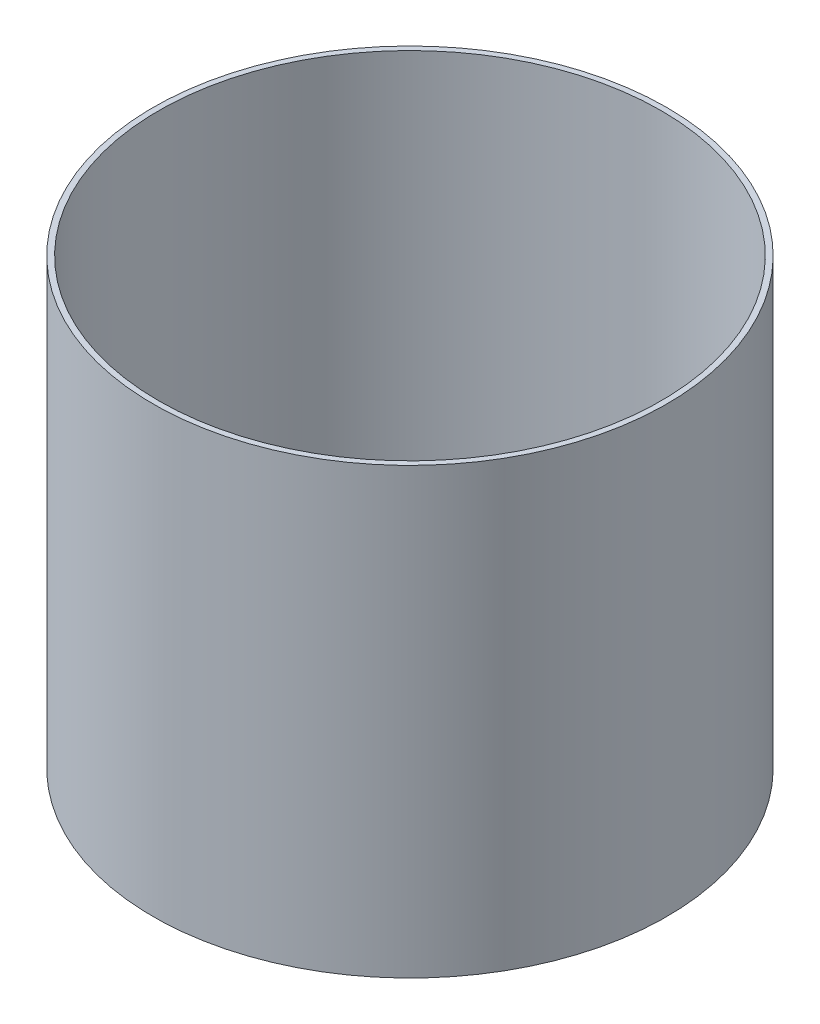
SolidWorks part; units mm, degrees
ref_plane "Front Plane" through (0, 0, 0) normal (0, 0, 1) x (1, 0, 0)
ref_plane "Top Plane" through (0, 0, 0) normal (0, 1, 0) x (1, 0, 0)
ref_plane "Right Plane" through (0, 0, 0) normal (1, 0, 0) x (0, 0, -1)
sketch "Sketch1" plane through (0, 0, 0) normal (0, 0, 1) x (1, 0, 0)
  line L0 (-85.7751, 73.1273) -> (-86.7751, 73.1273)
  line L1 (-86.7751, 73.1273) -> (-86.7751, -5.5436)
  line L2 (-86.7751, -5.5436) -> (-115, 1)
  line L3 (-115, 1) -> (-115, 0)
  line L4 (-115, 0) -> (-85.7751, -6.7754)
  line L5 (-85.7751, -6.7754) -> (-85.7751, 73.1273)
  line L6 (-132, 75) -> (-132, -5.359) construction
  dimension "D1" = 1
  dimension "D2" = 30
  dimension "D3" = 1
  dimension "D4" = 17
revolve "Revolve1" add sketch "Sketch1" angle 360 about L6
ref_plane "Plane1" through (0, -0.3058, 0) normal (0, 1, 0) x (1, 0, 0)
hole_wizard "Ø10.0 (10) Diameter Hole1" positions "Sketch3" profile "Sketch2" hole size "Ø10.0" standard "ANSI Metric"
sketch "Sketch3" plane through (0, -0.3058, 0) normal (0, 1, 0) x (1, 0, 0)
  circle A0 centre (-132, 0) radius 17 construction
  point P0 (-132.5, -35.9965)
  point P19 (-160.6459, -22.4456)
  point P20 (-167.6001, 8.0086)
  point P21 (-148.1259, 32.4336)
  point P22 (-116.8878, 32.4367)
  point P23 (-97.4086, 8.0157)
  point P24 (-104.3567, -22.44)
  dimension "D1" = 36
  dimension "D2" = 7
sketch "Sketch2" plane through (-132.5, -0.3058, 35.9965) normal (1, 0, 0) x (0, 0, 1)
  line L0 (0, 0) -> (0, 6.4696)
  line L1 (0, 6.4696) -> (5, 6.4696)
  line L2 (5, 6.4696) -> (5, 0)
  line L5 (5, 0) -> (0, 0)
  line L11 (0, -6.35) -> (0, 107.95) construction
  dimension "Thru Hole Dia." = 10
  dimension "Thru Hole Depth" = 6.4696
